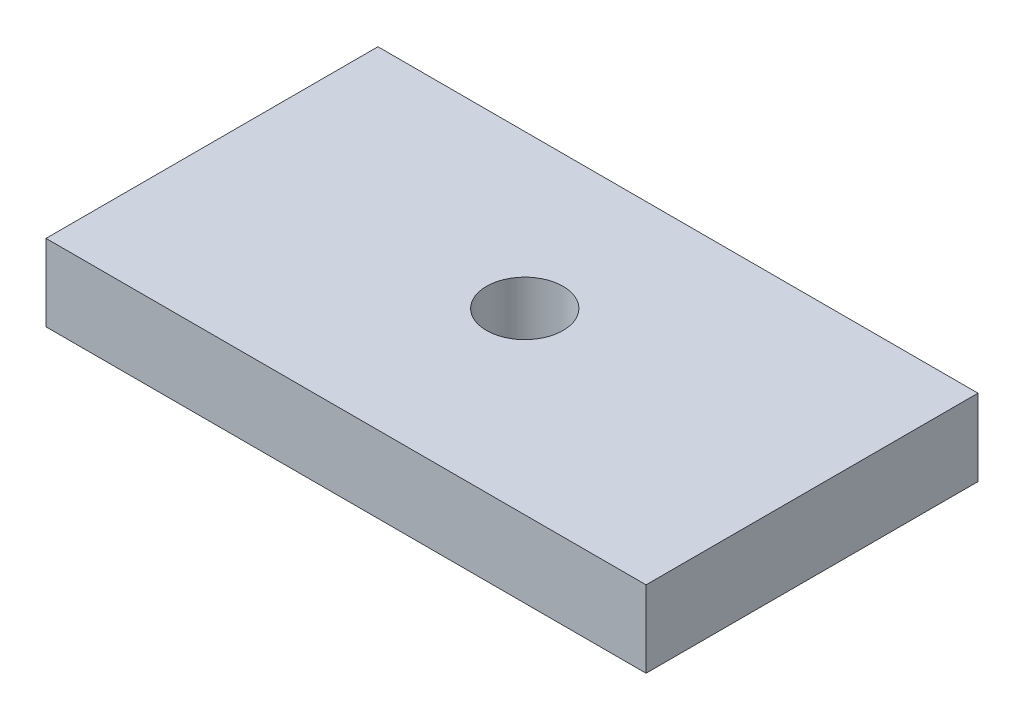
SolidWorks part; units mm, degrees
ref_plane "Plano frontal" through (0, 0, 0) normal (0, 0, 1) x (1, 0, 0)
ref_plane "Plano superior" through (0, 0, 0) normal (0, 1, 0) x (1, 0, 0)
ref_plane "Plano direito" through (0, 0, 0) normal (1, 0, 0) x (0, 0, -1)
sketch "Esboço1" plane through (0, 0, 0) normal (0, 0, 1) x (1, 0, 0)
  line L0 (-7.4579, 2.3859) -> (-7.2305, 2.3859)
  line L2 (4.0421, 2.3859) -> (10.0421, 2.3859)
  line L3 (10.0421, 2.3859) -> (10.0421, 5.3859)
  line L4 (10.0421, 5.3859) -> (-13.4579, 5.3859)
  line L5 (-13.4579, 5.3859) -> (-13.4579, 2.3859)
  line L6 (-13.4579, 2.3859) -> (-7.4579, 2.3859)
  line L8 (-7.2305, 2.3859) -> (4.0421, 2.3859)
  dimension "D1" = 23.5
  dimension "D2" = 6
  dimension "D3" = 6
  dimension "D6" = 3
extrude "Ressalto-extrusão2" add sketch "Esboço1" along normal blind 13
sketch "Esboço3" plane through (0, 5.3859, 0) normal (0, 1, 0) x (1, 0, 0)
  line L1 (-13.4579, -13) -> (-13.4579, 0) construction
  line L4 (10.0421, 0) -> (-13.4579, 0) construction
  circle A0 centre (-1.7079, -6) radius 1.5
  dimension "D1" = 3
  dimension "D2" = 6
  dimension "D3" = 11.75
extrude "Corte-extrusão2" cut sketch "Esboço3" against normal blind 13
